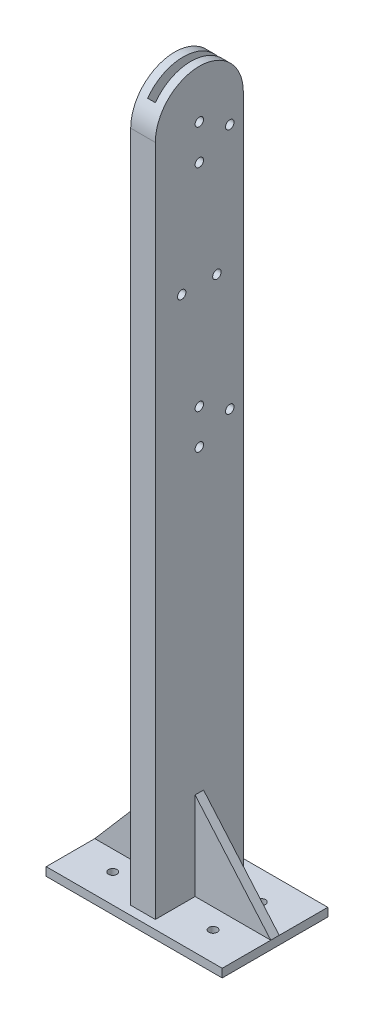
SolidWorks part; units mm, degrees
ref_plane "Front Plane" through (0, 0, 0) normal (0, 0, 1) x (1, 0, 0)
ref_plane "Top Plane" through (0, 0, 0) normal (0, 1, 0) x (1, 0, 0)
ref_plane "Right Plane" through (0, 0, 0) normal (1, 0, 0) x (0, 0, -1)
sketch "Sketch2" plane through (0, 0, 0) normal (0, 1, 0) x (1, 0, 0)
  line L0 (12, 12) -> (12, 113)
  line L1 (0, 0) -> (35, 0)
  line L2 (0, 0) -> (0, 125)
  line L3 (0, 125) -> (35, 125)
  line L4 (35, 0) -> (35, 125)
  line L5 (12, 113) -> (23, 113)
  line L6 (23, 12) -> (23, 113)
  line L7 (12, 12) -> (23, 12)
  dimension "D1" = 125
  dimension "D2" = 35
  dimension "D3" = 12
extrude "Boss-Extrude1" add sketch "Sketch2" along normal blind 1400
sketch "Sketch3" plane through (35, 0, 0) normal (1, 0, 0) x (0, 0, -1)
  line L0 (62.5, 1400) -> (62.5, 0) construction
  line L1 (0, 1400) -> (125, 1400) construction
  line L2 (0, 0) -> (125, 0) construction
  line L3 (37.5, 750) -> (87.5, 750) construction
  circle A0 centre (62.5, 950) radius 6
  circle A1 centre (62.5, 900) radius 6
  circle A2 centre (105.8013, 925) radius 6
  circle A3 centre (37.5, 750) radius 6
  circle A4 centre (87.5, 750) radius 6
  circle A8 centre (105.8013, 575) radius 6
  circle A9 centre (62.5, 600) radius 6
  circle A10 centre (62.5, 550) radius 6
  point P23 (62.5, 750)
  point P24 (62.5, 750)
  dimension "D1" = 12
  dimension "D6" = 150
  dimension "D7" = 550
  dimension "D2" = 50
  dimension "D3" = 50
  dimension "D4" = 50
  dimension "D5" = 50
extrude "Cut-Extrude1" cut sketch "Sketch3" against normal through all
sketch "Sketch4" plane through (0, 0, 0) normal (0, -1, 0) x (-1, 0, 0)
  line L0 (-35, 0) -> (0, 125) construction
  line L2 (107.5, -12.5) -> (-142.5, -12.5)
  line L3 (107.5, -12.5) -> (107.5, 137.5)
  line L4 (107.5, 137.5) -> (-142.5, 137.5)
  line L5 (-142.5, -12.5) -> (-142.5, 137.5)
  line L6 (107.5, -12.5) -> (-142.5, 137.5) construction
  line L7 (107.5, 137.5) -> (-142.5, -12.5) construction
  point P4 (-17.5, 62.5)
  dimension "D1" = 250
  dimension "D2" = 150
extrude "Boss-Extrude2" add sketch "Sketch4" along normal blind 12
sketch "Sketch5" plane through (0, 1400, 0) normal (0, 1, 0) x (1, 0, 0)
  line L0 (0, 125) -> (35, 0) construction
  line L2 (-107.5, -12.5) -> (142.5, -12.5)
  line L3 (-107.5, -12.5) -> (-107.5, 137.5)
  line L4 (-107.5, 137.5) -> (142.5, 137.5)
  line L5 (142.5, -12.5) -> (142.5, 137.5)
  line L6 (-107.5, -12.5) -> (142.5, 137.5) construction
  line L7 (-107.5, 137.5) -> (142.5, -12.5) construction
  point P4 (17.5, 62.5)
extrude "Boss-Extrude3" add sketch "Sketch5" along normal blind 12
sketch "Sketch7" plane through (0, 0, -125) normal (0, 0, -1) x (-1, 0, 0)
  line L0 (-35, 0) -> (-35, 125)
  line L1 (-35, 1400) -> (-35, 0) construction
  line L2 (-35, 125) -> (-142.5, 0)
  line L3 (-142.5, 0) -> (-35, 0)
  line L4 (-17.5, 0) -> (-17.5, 1400) construction
  line L5 (-35, 0) -> (0, 0) construction
  line L6 (-35, 1400) -> (0, 1400) construction
  line L7 (0, 125) -> (107.5, 0)
  line L8 (0, 0) -> (0, 125)
  line L9 (107.5, 0) -> (0, 0)
  dimension "D1" = 125
extrude "Boss-Extrude4" add sketch "Sketch7" along normal mid plane 12 from offset 62.5 offset against normal yes
sketch "Sketch8" plane through (0, 0, 0) normal (0, 1, 0) x (1, 0, 0)
  line L0 (0, 0) -> (0, 56.5) construction
  line L1 (0, 28.25) -> (-107.5, 28.25) construction
  line L2 (-107.5, -12.5) -> (-107.5, 56.5) construction
  line L3 (35, 28.25) -> (142.5, 28.25) construction
  line L4 (35, 0) -> (35, 56.5) construction
  line L5 (142.5, 56.5) -> (142.5, -12.5) construction
  line L9 (0, 68.5) -> (0, 125) construction
  line L10 (0, 96.75) -> (-107.5, 96.75) construction
  line L11 (-107.5, 68.5) -> (-107.5, 137.5) construction
  circle A0 centre (-53.75, 28.25) radius 6
  circle A1 centre (-53.75, 96.75) radius 6
  circle A2 centre (88.75, 28.25) radius 6
  circle A3 centre (88.75, 96.75) radius 6
  dimension "D1" = 12
extrude "Cut-Extrude2" cut sketch "Sketch8" against normal up to surface (12 mm away) up to face at (17.5, -12, -62.5)
sketch "Sketch9" plane through (35, 0, 0) normal (1, 0, 0) x (0, 0, -1)
  line L0 (0, 1400) -> (0, 0) construction
  line L1 (-163.7286, 1439.7096) -> (272.3027, 1439.7096)
  line L2 (-163.7286, 1439.7096) -> (-163.7286, 682.8526)
  line L3 (-163.7286, 682.8526) -> (0, 682.8526)
  line L4 (272.3027, 1439.7096) -> (272.3027, 682.8526)
  line L6 (0, 682.8526) -> (0, 956)
  line L8 (125, 682.8526) -> (125, 956)
  line L9 (125, 682.8526) -> (272.3027, 682.8526)
  line L10 (125, 1400) -> (125, 0) construction
  arc A0 (125, 956) -> (0, 956) centre (62.5, 956) ccw
  circle A1 centre (62.5, 950) radius 6 construction
extrude "Cut-Extrude3" cut sketch "Sketch9" against normal through all both and the other way through all
equation "\"mbtOD\" = 850"
equation "\"mbtT\" = 6"
equation "\"mbtL\" = 1500"
equation "\"mbtFlangeOD\" = 950"
equation "\"mbtFlangeT\" = 12"
equation "\"mbtFlangeBoltCircleDia\" = 650"
equation "\"mbtFlangeHoleDia\" = 12"
equation "\"mbtOringSize\" = 10 "
equation "\"mbtOringDia\" = 620"
equation "\"mbtWidth\" = 2250"
equation "\"skiWidth\" = 1250"
equation "\"D1@Boss-Extrude1\"=\"mbtFlangeOD\"+450mm"
equation "\"D1@Boss-Extrude2\"=\"mbtFlangeT\""
